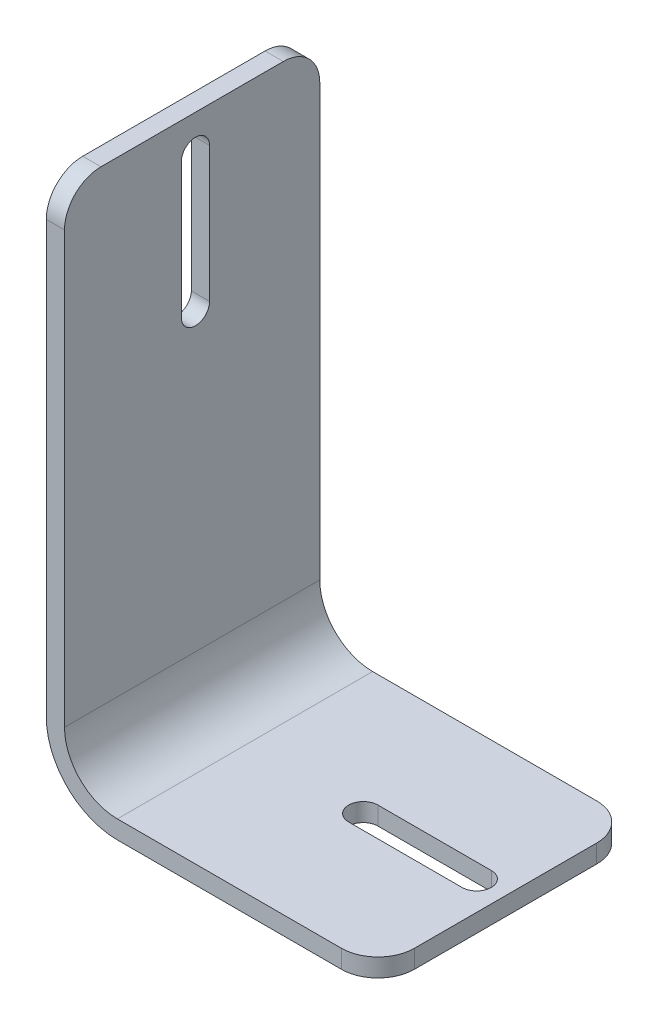
SolidWorks part; units mm, degrees
ref_plane "Front Plane" through (0, 0, 0) normal (0, 0, 1) x (1, 0, 0)
ref_plane "Top Plane" through (0, 0, 0) normal (0, 1, 0) x (1, 0, 0)
ref_plane "Right Plane" through (0, 0, 0) normal (1, 0, 0) x (0, 0, -1)
sketch "Sketch1" plane through (0, 0, 0) normal (0, 0, 1) x (1, 0, 0)
  line L0 (0, 41.919) -> (0, -23.1693)
  line L1 (7.366, -30.5352) -> (43.66, -30.5352)
  arc A0 (0, -23.1693) -> (7.366, -30.5352) centre (7.366, -23.1693) ccw
extrude "Extrude-Thin1" add sketch "Sketch1" along normal blind 35.56 thin
fillet "Fillet1" radius 5.08 4 edges at (43.66, -31.8052, 35.56) (43.66, -31.8052, 0) (-1.27, 41.919, 0) (-1.27, 41.919, 35.56)
sketch "Sketch2" plane through (0, 0, 0) normal (1, 0, 0) x (0, 0, -1)
  line L0 (-17.3177, 36.9343) -> (-17.3177, 18.1195) construction
  line L1 (-15.3536, 36.9343) -> (-15.3536, 18.1195)
  line L2 (-19.2819, 36.9343) -> (-19.2819, 18.1195)
  arc A0 (-15.3536, 36.9343) -> (-19.2819, 36.9343) centre (-17.3177, 36.9343) ccw
  arc A1 (-19.2819, 18.1195) -> (-15.3536, 18.1195) centre (-17.3177, 18.1195) ccw
  point P2 (-17.3177, 27.5269)
  point P7 (-17.3177, 27.5269)
extrude "Cut-Extrude1" cut sketch "Sketch2" against normal through all
sketch "Sketch3" plane through (0, -30.5352, 0) normal (0, 1, 0) x (1, 0, 0)
  line L0 (39.6374, -17.78) -> (23.8444, -17.78) construction
  line L1 (39.6374, -19.8217) -> (23.8444, -19.8217)
  line L2 (39.6374, -15.7383) -> (23.8444, -15.7383)
  arc A0 (39.6374, -19.8217) -> (39.6374, -15.7383) centre (39.6374, -17.78) ccw
  arc A1 (23.8444, -15.7383) -> (23.8444, -19.8217) centre (23.8444, -17.78) ccw
  point P2 (31.7409, -17.78)
extrude "Cut-Extrude2" cut sketch "Sketch3" against normal through all
